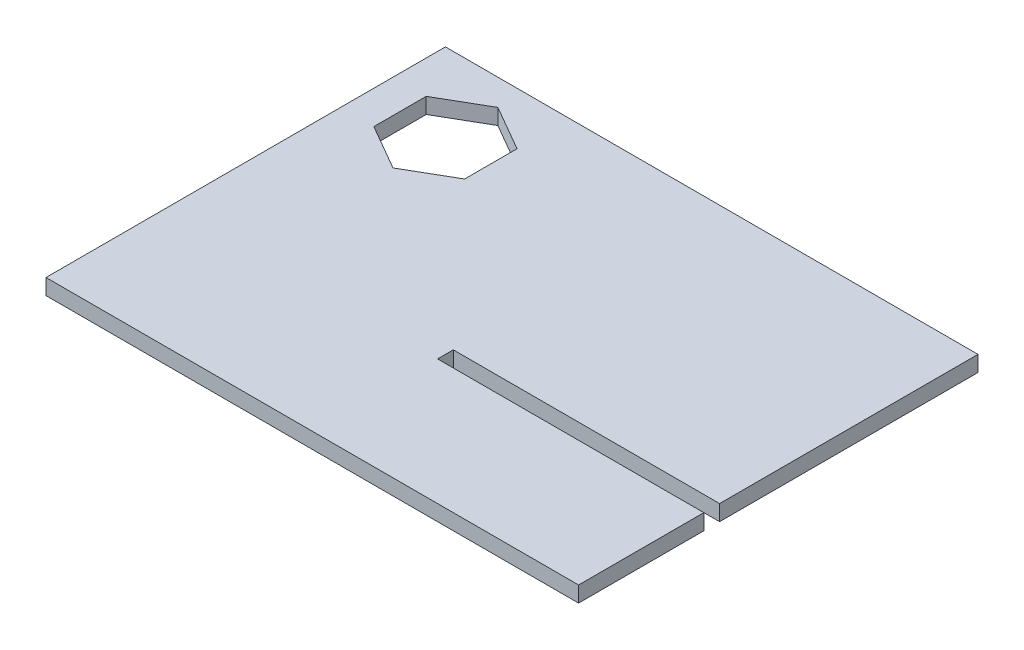
SolidWorks part; units mm, degrees
ref_plane "Front Plane" through (0, 0, 0) normal (0, 0, 1) x (1, 0, 0)
ref_plane "Top Plane" through (0, 0, 0) normal (0, 1, 0) x (1, 0, 0)
ref_plane "Right Plane" through (0, 0, 0) normal (1, 0, 0) x (0, 0, -1)
sketch "Sketch1" plane through (0, 0, 0) normal (0, 1, 0) x (1, 0, 0)
  line L1 (0, 0) -> (101.6, 0)
  line L2 (0, 0) -> (0, 76.2)
  line L3 (0, 76.2) -> (101.6, 76.2)
  line L4 (101.6, 0) -> (101.6, 76.2)
  dimension "D1" = 76.2
  dimension "D2" = 101.6
extrude "Boss-Extrude1" add sketch "Sketch1" along normal blind 3
sketch "Sketch2" plane through (0, 3, 0) normal (0, 1, 0) x (1, 0, 0)
  line L0 (101.6, 0) -> (101.6, 76.2) construction
  line L1 (101.6, 23.9) -> (50.8, 23.9)
  line L2 (101.6, 23.9) -> (101.6, 26.9)
  line L3 (101.6, 26.9) -> (50.8, 26.9)
  line L4 (50.8, 23.9) -> (50.8, 26.9)
  line L6 (0, 0) -> (101.6, 0) construction
  point P6 (101.6, 25.4)
  dimension "D1" = 50.8
  dimension "D2" = 3
  dimension "D3" = 25.4
extrude "Cut-Extrude1" cut sketch "Sketch2" against normal blind 3
sketch "Sketch3" plane through (0, 3, 0) normal (0, 1, 0) x (1, 0, 0)
  line L1 (15, 51.2) -> (23.6603, 56.2)
  line L2 (23.6603, 56.2) -> (23.6603, 66.2)
  line L3 (23.6603, 66.2) -> (15, 71.2)
  line L4 (15, 71.2) -> (6.3397, 66.2)
  line L5 (6.3397, 66.2) -> (6.3397, 56.2)
  line L6 (6.3397, 56.2) -> (15, 51.2)
  line L8 (0, 76.2) -> (0, 0) construction
  line L9 (101.6, 76.2) -> (0, 76.2) construction
  circle A0 centre (15, 61.2) radius 8.6603 construction
  dimension "D1" = 10
  dimension "D2" = 15
  dimension "D3" = 15
extrude "Cut-Extrude2" cut sketch "Sketch3" against normal blind 3
